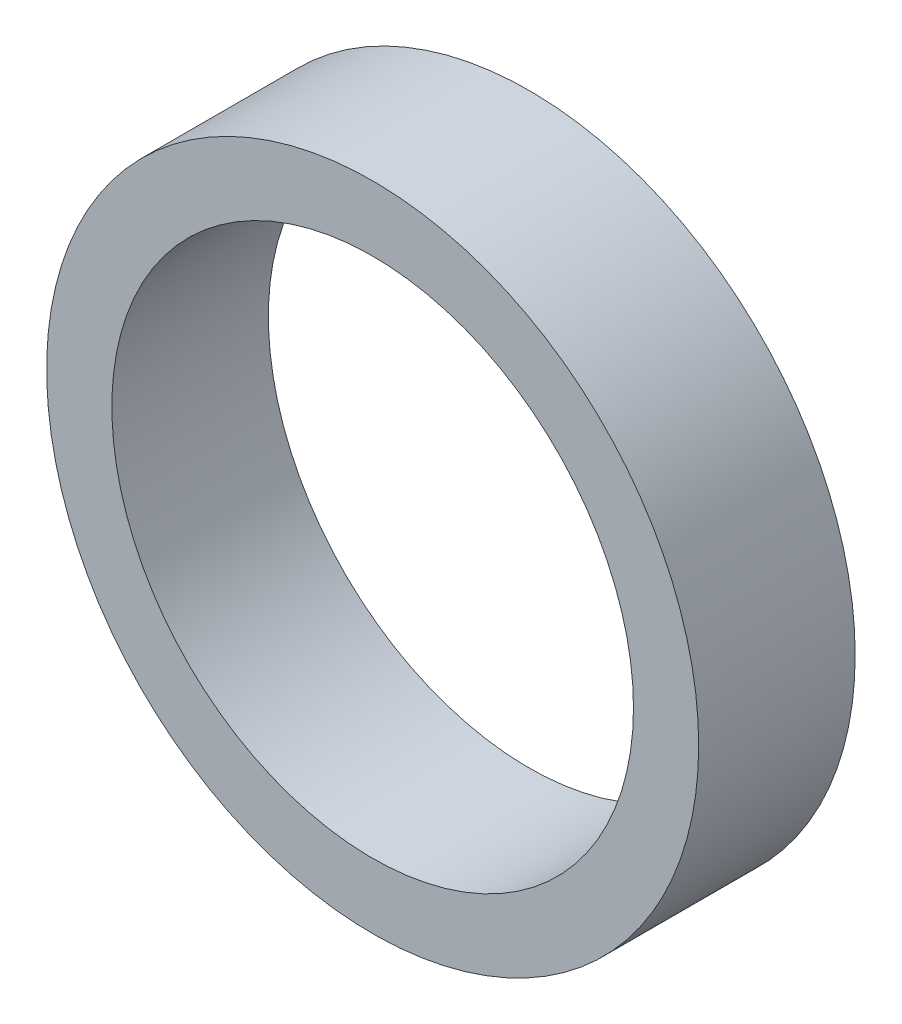
SolidWorks part; units mm, degrees
ref_plane "Front Plane" through (0, 0, 0) normal (0, 0, 1) x (1, 0, 0)
ref_plane "Top Plane" through (0, 0, 0) normal (0, 1, 0) x (1, 0, 0)
ref_plane "Right Plane" through (0, 0, 0) normal (1, 0, 0) x (0, 0, -1)
sketch "Sketch1" plane through (0, 0, 0) normal (0, 0, 1) x (1, 0, 0)
  circle A0 centre (0, 0) radius 6
  circle A1 centre (0, 0) radius 7.5
  dimension "D1" = 12
  dimension "D2" = 15
extrude "Boss-Extrude1" add sketch "Sketch1" along normal blind 3.6
